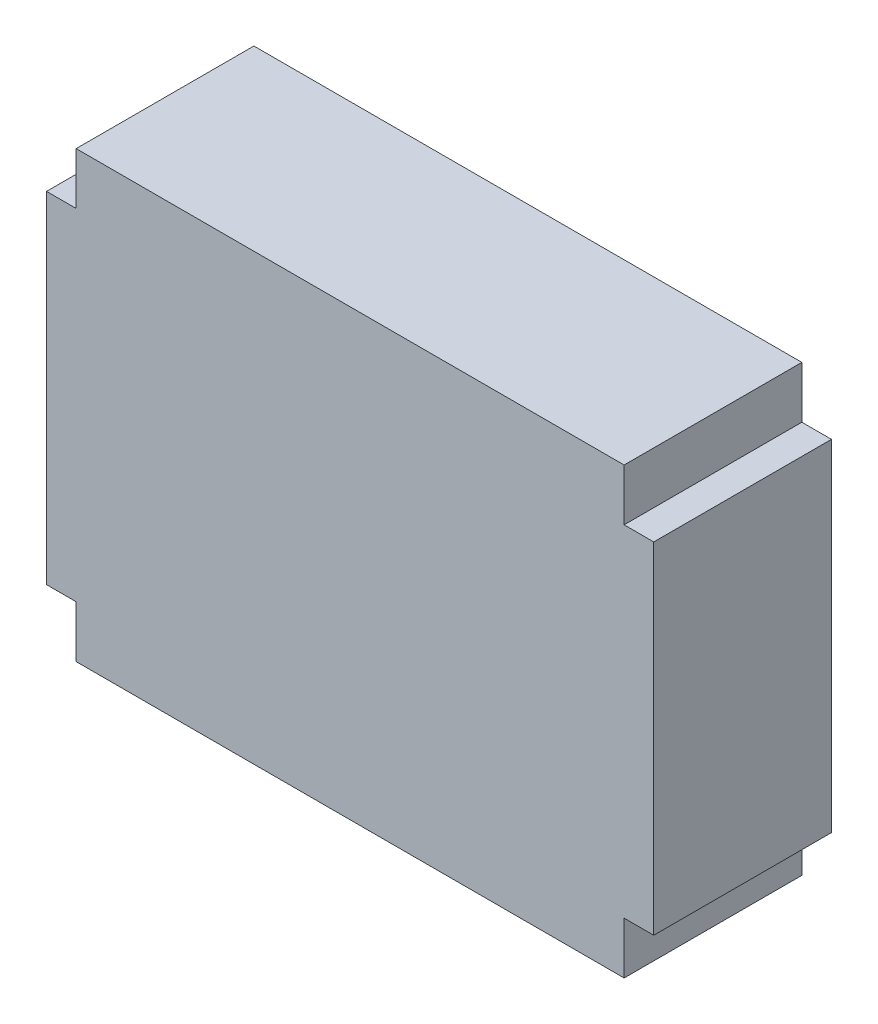
SolidWorks part; units mm, degrees
ref_plane "前视基准面" through (0, 0, 0) normal (0, 0, 1) x (1, 0, 0)
ref_plane "上视基准面" through (0, 0, 0) normal (0, 1, 0) x (1, 0, 0)
ref_plane "右视基准面" through (0, 0, 0) normal (1, 0, 0) x (0, 0, -1)
sketch "草图1" plane through (0, 0, 0) normal (0, 0, 1) x (1, 0, 0)
  line L0 (1.85, -1.5) -> (1.85, -1.15)
  line L1 (1.85, -1.15) -> (2.05, -1.15)
  line L2 (2.05, -1.15) -> (2.05, 1.15)
  line L3 (2.05, 1.15) -> (1.85, 1.15)
  line L4 (1.85, 1.15) -> (1.85, 1.5)
  line L5 (1.85, 1.5) -> (-1.85, 1.5)
  line L6 (-1.85, 1.5) -> (-1.85, 1.15)
  line L7 (-1.85, 1.15) -> (-2.05, 1.15)
  line L8 (-2.05, 1.15) -> (-2.05, -1.15)
  line L9 (-2.05, -1.15) -> (-1.85, -1.15)
  line L10 (-1.85, -1.15) -> (-1.85, -1.5)
  line L11 (-1.85, -1.5) -> (1.85, -1.5)
extrude "Component_Outline" add sketch "草图1" along normal blind 1.2 separate body
sketch3d "3D草图1"
  line L0 (0, 0, 0) -> (1, 0, 0)
  line L1 (0, 0, 0) -> (0, 1, 0)
  line L2 (0, 0, 0) -> (0, 0, 1)
  point P0 (0, 0, 0)
